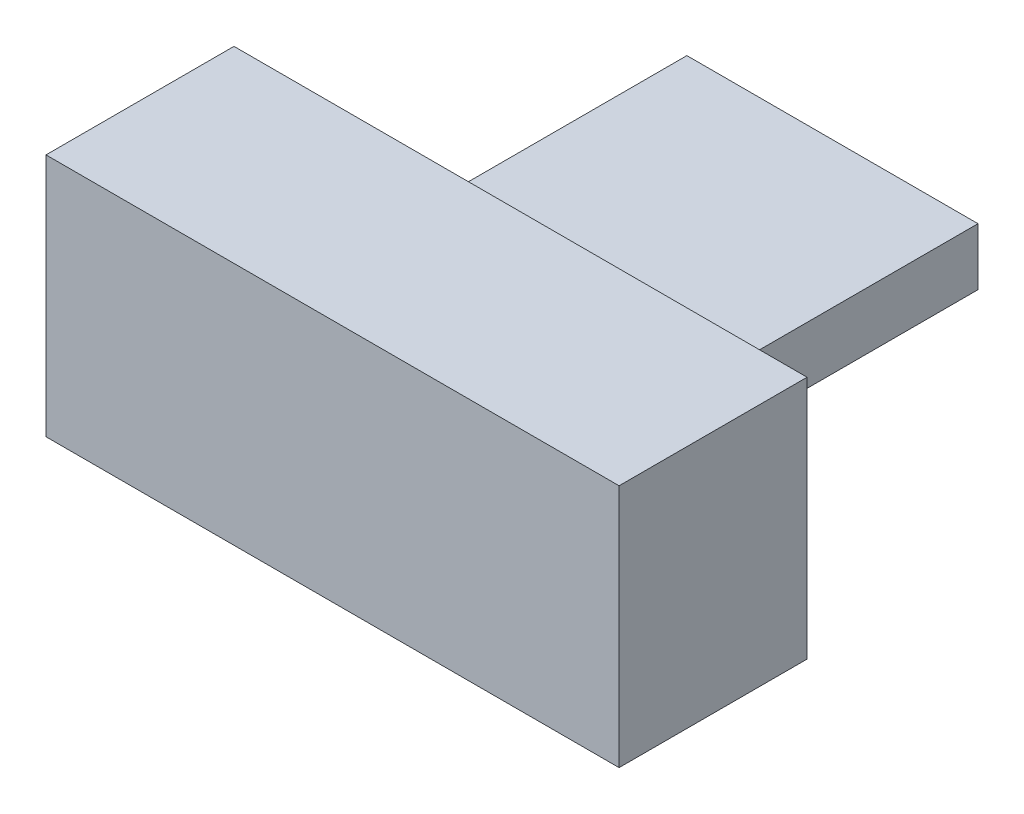
SolidWorks part; units mm, degrees
ref_plane "Front Plane" through (0, 0, 0) normal (0, 0, 1) x (1, 0, 0)
ref_plane "Top Plane" through (0, 0, 0) normal (0, 1, 0) x (1, 0, 0)
ref_plane "Right Plane" through (0, 0, 0) normal (1, 0, 0) x (0, 0, -1)
sketch "Sketch1" plane through (0, 0, 0) normal (0, 1, 0) x (1, 0, 0)
  line L0 (0, 0) -> (0, 25.0245) construction
  line L1 (-35.0012, 11.4808) -> (35.0012, 11.4808)
  line L2 (-35.0012, 11.4808) -> (-35.0012, -11.4808)
  line L3 (-35.0012, -11.4808) -> (35.0012, -11.4808)
  line L4 (35.0012, 11.4808) -> (35.0012, -11.4808)
  line L5 (0, 0) -> (61.4909, 0) construction
  dimension "D1" = 22.9616
  dimension "D2" = 70.0024
extrude "Boss-Extrude1" add sketch "Sketch1" along normal mid plane 29.8196
sketch "Sketch2" plane through (0, 0, -11.4808) normal (0, 0, -1) x (-1, 0, 0)
  line L0 (0, 0) -> (0, 19.882) construction
  line L1 (-17.78, -3.4925) -> (17.78, -3.4925)
  line L2 (-17.78, -3.4925) -> (-17.78, 3.4925)
  line L3 (-17.78, 3.4925) -> (17.78, 3.4925)
  line L4 (17.78, -3.4925) -> (17.78, 3.4925)
  line L5 (0, 0) -> (24.1088, 0) construction
  dimension "D1" = 6.985
  dimension "D2" = 35.56
extrude "Boss-Extrude2" add sketch "Sketch2" along normal blind 38.1
